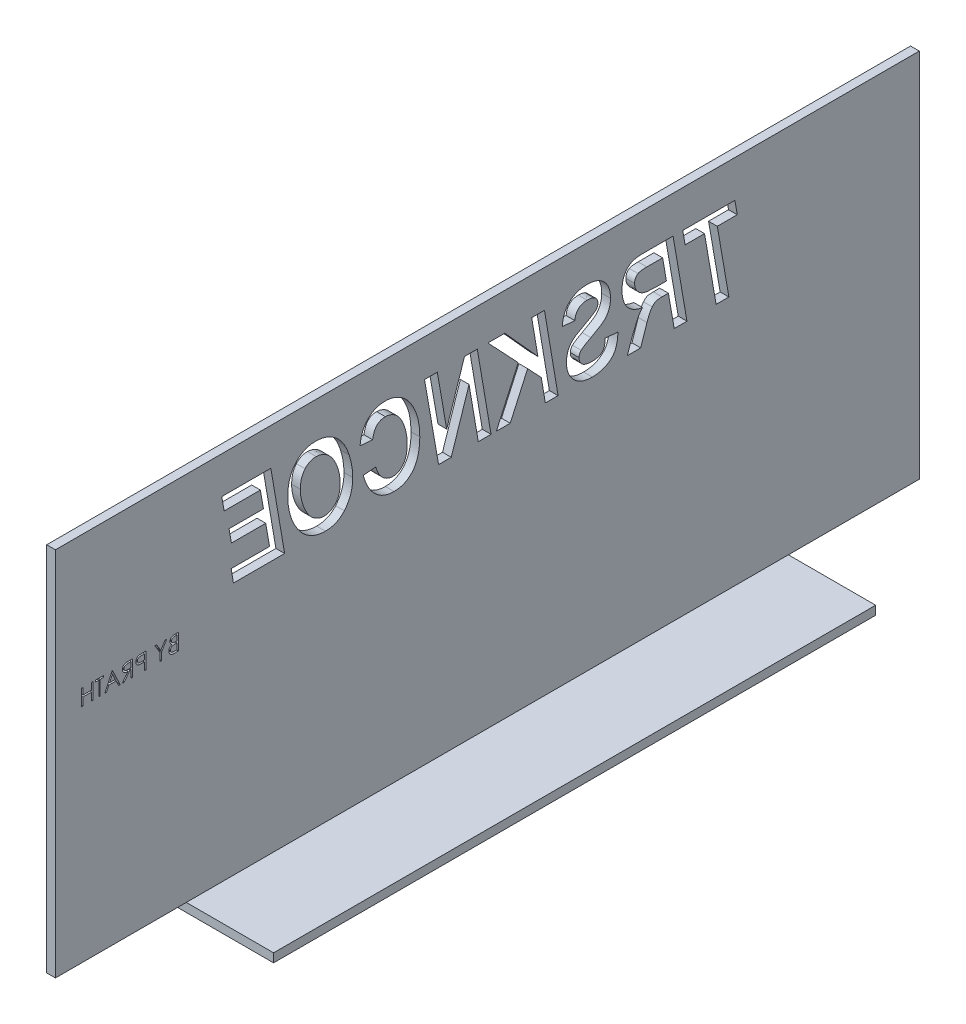
SolidWorks part; units mm, degrees
material "Acrylic (Medium-high impact)"
ref_plane "Front Plane" through (0, 0, 0) normal (0, 0, 1) x (1, 0, 0)
ref_plane "Top Plane" through (0, 0, 0) normal (0, 1, 0) x (1, 0, 0)
ref_plane "Right Plane" through (0, 0, 0) normal (1, 0, 0) x (0, 0, -1)
sketch "Sketch1" plane through (0, 0, 0) normal (0, 0, 1) x (1, 0, 0)
  line L0 (-48.6214, 40.1389) -> (-48.6214, -44.8611)
  line L1 (-48.6214, -44.8611) -> (-28.6214, -44.8611)
  line L2 (-50.6214, 40.1389) -> (-50.6214, -46.8611)
  line L3 (-50.6214, -46.8611) -> (-28.6214, -46.8611)
  line L4 (-50.6214, 40.1389) -> (-48.6214, 40.1389)
  line L5 (-28.6214, -46.8611) -> (-28.6214, -44.8611)
  dimension "D1" = 85
  dimension "D2" = 20
  dimension "D3" = 2
extrude "Boss-Extrude1" add sketch "Sketch1" along normal blind 198
sketch "Sketch2" plane through (0, -46.8611, 0) normal (0, -1, 0) x (-1, 0, 0)
  line L1 (50.6214, 0) -> (28.6214, 0)
  line L2 (50.6214, 0) -> (50.6214, -30)
  line L3 (50.6214, -30) -> (28.6214, -30)
  line L4 (28.6214, 0) -> (28.6214, -30)
  line L5 (50.6214, -198) -> (28.6214, -198)
  line L6 (50.6214, -198) -> (50.6214, -168)
  line L7 (50.6214, -168) -> (28.6214, -168)
  line L8 (28.6214, -198) -> (28.6214, -168)
  dimension "D1" = 22
  dimension "D2" = 22
  dimension "D3" = 30
  dimension "D4" = 30
extrude "Cut-Extrude3" cut sketch "Sketch2" against normal blind 2
sketch "Sketch3" plane through (-50.6214, 0, 0) normal (-1, 0, 0) x (0, 0, 1)
  line L0 (0, 13.1389) -> (198, 13.1389) construction
  line L1 (0, 40.1389) -> (0, -44.8611) construction
  line L2 (198, 40.1389) -> (198, -44.8611) construction
  line L3 (198, 40.1389) -> (0, 40.1389) construction
  text T0 "TRSKNCOE" font "Arial Narrow" height in points 72
  text T1 "                                                                                                                     \r\n                                                                                                                   BY PRATH" font "Century Gothic" height in points 14
  dimension "D1" = 27
extrude "Cut-Extrude4" cut sketch "Sketch3" against normal blind 22
